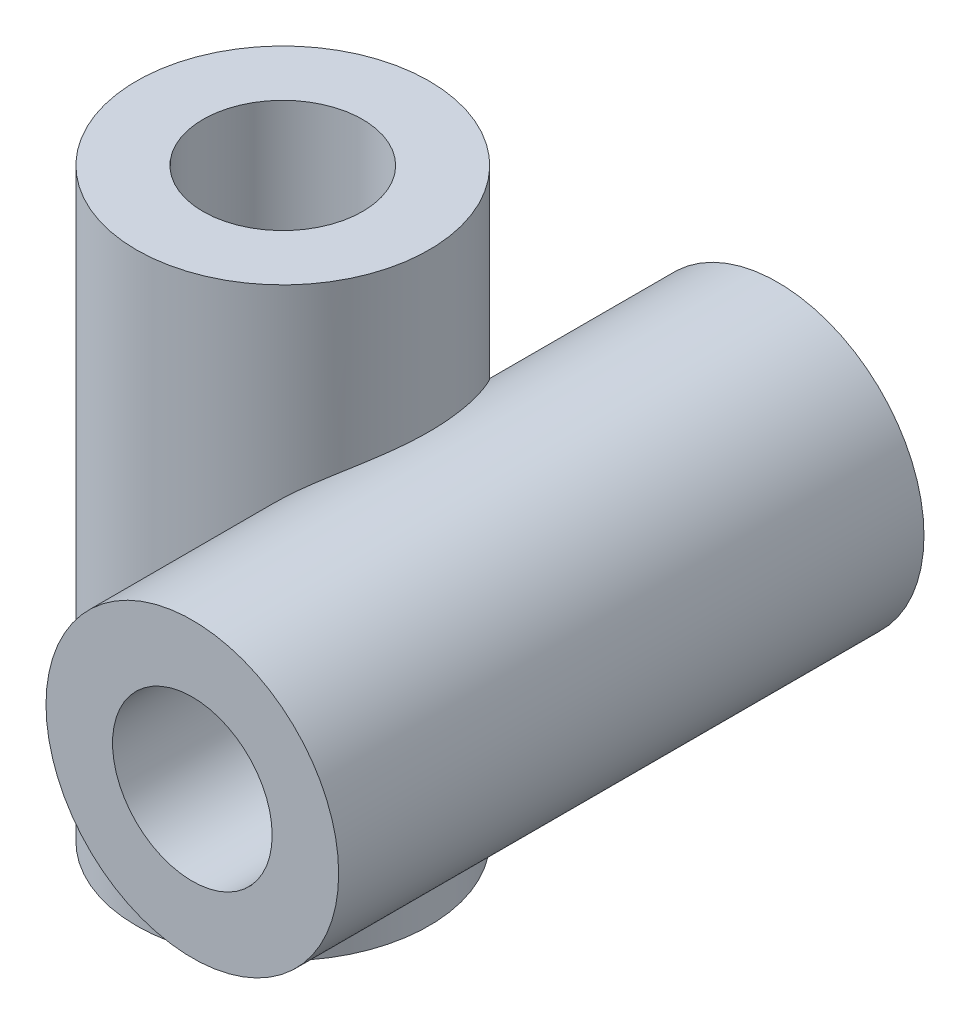
SolidWorks part; units mm, degrees
ref_plane "Front Plane" through (0, 0, 0) normal (0, 0, 1) x (1, 0, 0)
ref_plane "Top Plane" through (0, 0, 0) normal (0, 1, 0) x (1, 0, 0)
ref_plane "Right Plane" through (0, 0, 0) normal (1, 0, 0) x (0, 0, -1)
sketch "Sketch2" plane through (0, 0, 0) normal (0, 1, 0) x (1, 0, 0)
  circle A0 centre (0, 0) radius 27.5
  circle A1 centre (0, 0) radius 15
  dimension "D1" = 55
  dimension "D2" = 30
extrude "Boss-Extrude1" add sketch "Sketch2" along normal blind 110
sketch "Sketch3" plane through (0, 0, 0) normal (0, 0, 1) x (1, 0, 0)
  line L0 (27.5, 110) -> (-27.5, 110) construction
  circle A0 centre (38, 55) radius 27.5
  circle A1 centre (38, 55) radius 15
  dimension "D1" = 55
  dimension "D2" = 30
  dimension "D3" = 38
  dimension "D4" = 55
extrude "Boss-Extrude2" add sketch "Sketch3" along normal mid plane 110
